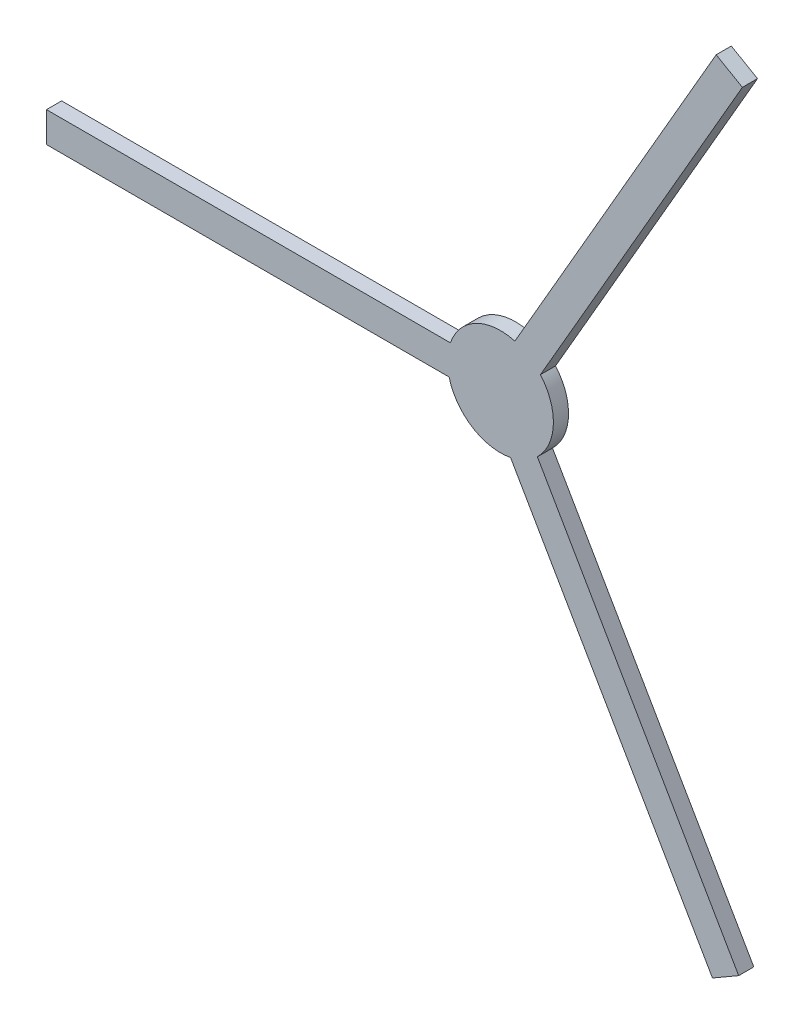
SolidWorks part; units mm, degrees
ref_plane "Front Plane" through (0, 0, 0) normal (0, 0, 1) x (1, 0, 0)
ref_plane "Top Plane" through (0, 0, 0) normal (0, 1, 0) x (1, 0, 0)
ref_plane "Right Plane" through (0, 0, 0) normal (1, 0, 0) x (0, 0, -1)
sketch "Sketch1" plane through (0, 0, 0) normal (0, 0, 1) x (1, 0, 0)
  line L0 (26.4271, 22.9479) -> (159.8836, 254.1013)
  line L1 (-33.087, 11.4126) -> (-300, 11.4126)
  line L3 (-33.9302, -8.5874) -> (-300, -8.5874)
  line L4 (-300, 11.4126) -> (-300, -8.5874)
  line L5 (9.5282, 33.6781) -> (142.5631, 264.1013)
  line L6 (159.8836, 254.1013) -> (142.5631, 264.1013)
  line L7 (6.6599, -34.3605) -> (140.1164, -265.5139)
  line L8 (24.402, -25.0907) -> (157.4369, -255.5139)
  line L9 (140.1164, -265.5139) -> (157.4369, -255.5139)
  arc A0 (-33.9302, -8.5874) -> (6.6599, -34.3605) centre (0, 0) ccw
  arc A1 (9.5282, 33.6781) -> (-33.087, 11.4126) centre (0, 0) ccw
  arc A2 (24.402, -25.0907) -> (26.4271, 22.9479) centre (0, 0) ccw
  dimension "D1" = 70
  dimension "D2" = 300
  dimension "D3" = 20
  dimension "D4" = 3
extrude "Boss-Extrude3" add sketch "Sketch1" along normal blind 10
